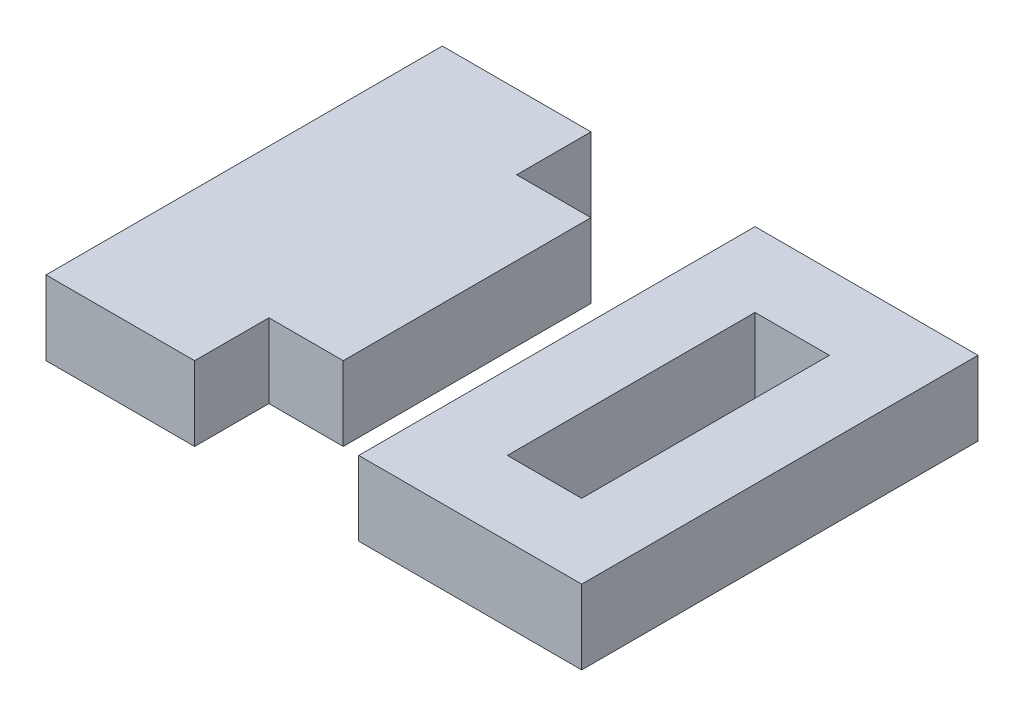
SolidWorks part; units mm, degrees
ref_plane "Front Plane" through (0, 0, 0) normal (0, 0, 1) x (1, 0, 0)
ref_plane "Top Plane" through (0, 0, 0) normal (0, 1, 0) x (1, 0, 0)
ref_plane "Right Plane" through (0, 0, 0) normal (1, 0, 0) x (0, 0, -1)
sketch "Sketch1" plane through (0, 0, 0) normal (0, 1, 0) x (1, 0, 0)
  line L0 (-31.25, 32) -> (-31.25, 0)
  line L1 (0, 0) -> (-18, 0)
  line L2 (0, 0) -> (0, 32)
  line L3 (0, 32) -> (-18, 32)
  line L4 (-18, 0) -> (-18, 32)
  line L5 (-12, 26) -> (-6, 26)
  line L6 (-12, 26) -> (-12, 6)
  line L7 (-12, 6) -> (-6, 6)
  line L8 (-6, 26) -> (-6, 6)
  line L9 (-31.25, 32) -> (-43.25, 32)
  line L10 (-25.25, 26) -> (-25.25, 6)
  line L11 (-31.25, 0) -> (-43.25, 0)
  line L12 (-43.25, 32) -> (-43.25, 0)
  line L13 (-25.25, 26) -> (-31.25, 26)
  line L14 (-25.25, 26) -> (-25.25, 6)
  line L15 (-25.25, 6) -> (-31.25, 6)
  line L16 (-31.25, 26) -> (-31.25, 6)
  dimension "D1" = 6
  dimension "D2" = 6
  dimension "D3" = 6
  dimension "D4" = 20
  dimension "D5" = 6
  dimension "D6" = 6
  dimension "D8" = 32
  dimension "D9" = 6
  dimension "D10" = 6
extrude "Boss-Extrude1" add sketch "Sketch1" along normal blind 6 contours L9 L12 L11 L0 | L15 L10 L13 L0 | L4 L1 L2 L3 L5 L8 L7 L6
